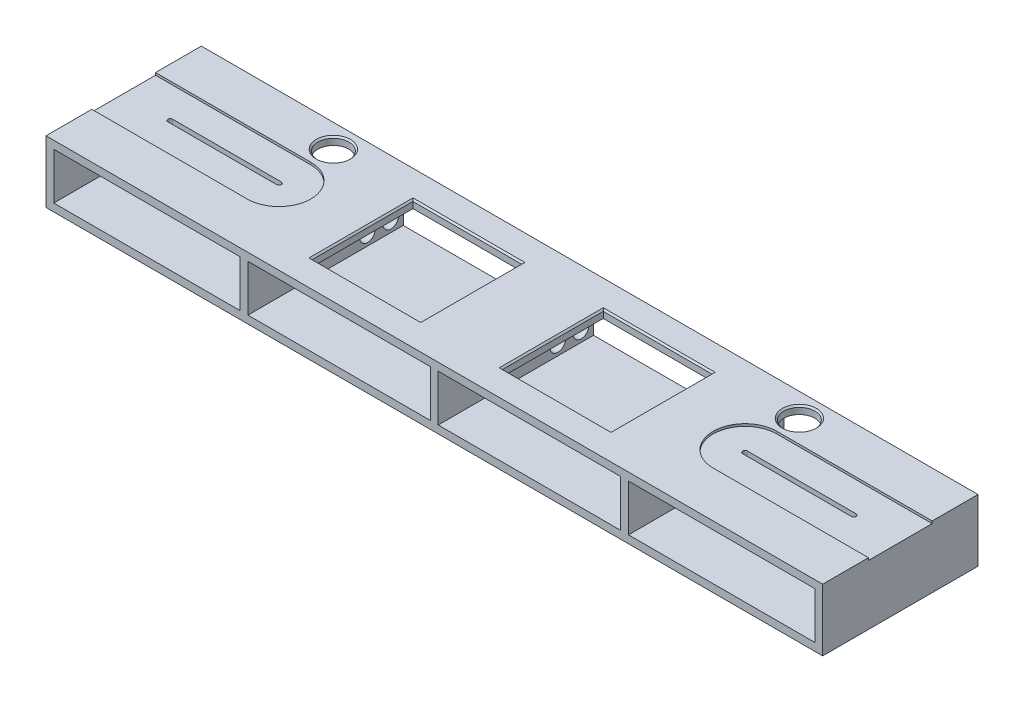
SolidWorks part; units mm, degrees
ref_plane "Alzado" through (0, 0, 0) normal (0, 0, 1) x (1, 0, 0)
ref_plane "Planta" through (0, 0, 0) normal (0, 1, 0) x (1, 0, 0)
ref_plane "Vista lateral" through (0, 0, 0) normal (1, 0, 0) x (0, 0, -1)
sketch "Croquis1" plane through (0, 0, 0) normal (0, 1, 0) x (1, 0, 0)
  line L1 (250, -50) -> (-250, -50)
  line L2 (250, -50) -> (250, 50)
  line L3 (250, 50) -> (-250, 50)
  line L4 (-250, -50) -> (-250, 50)
  line L5 (250, -50) -> (-250, 50) construction
  line L6 (250, 50) -> (-250, -50) construction
  point P0 (0, 0)
  dimension "D1" = 500
  dimension "D2" = 100
extrude "Saliente-Extruir1" add sketch "Croquis1" along normal blind 40
shell "Vaciado1" thickness 5
sketch "Croquis2" plane through (0, 0, 50) normal (0, 0, 1) x (1, 0, 0)
  line L0 (-245, 35) -> (125, 35) construction
  line L1 (-122.5, 35) -> (-122.5, 5)
  line L2 (-245, 5) -> (245, 5) construction
  line L3 (0, 35) -> (0, 5)
  line L4 (122.5, 35) -> (122.5, 5)
  line L6 (-125, 35) -> (-125, 5)
  line L7 (-2.5, 35) -> (-2.5, 5)
  line L8 (120, 35) -> (120, 5)
  line L10 (-120, 35) -> (-120, 5)
  line L11 (2.5, 35) -> (2.5, 5)
  line L12 (125, 35) -> (125, 5)
  line L14 (-125, 35) -> (-120, 35)
  line L15 (-125, 5) -> (-120, 5)
  line L16 (-2.5, 35) -> (2.5, 35)
  line L17 (-2.5, 5) -> (2.5, 5)
  line L18 (120, 35) -> (125, 35)
  line L19 (120, 5) -> (125, 5)
  line L22 (-245, 35) -> (-245, 5) construction
  line M10 (245, 5) -> (-245, 5)
  line M12 (-245, 35) -> (245, 35)
  dimension "D3" = 122.5
  dimension "D4" = 122.5
  dimension "D5" = 122.5
  dimension "D1" = 2.5
  dimension "D2" = 2.5
extrude "Saliente-Extruir2" add sketch "Croquis2" against normal blind 100 contours L6 L1 M12 M10 | L10 L1 M12 M10 | L7 L3 M12 M10 | L11 L3 M12 M10 | L8 L4 M12 M10 | L12 L4 M12 M10
sketch "Croquis3" plane through (0, 40, 0) normal (0, 1, 0) x (1, 0, 0)
  line L0 (-250, 50) -> (-250, -50) construction
  line L1 (-250, 20.5) -> (-150, 20.5)
  line L2 (-250, 20.5) -> (-250, -20.5)
  line L3 (-250, -20.5) -> (-150, -20.5)
  line L5 (250, -50) -> (250, 50) construction
  line L6 (250, 20.5) -> (150, 20.5)
  line L7 (250, 20.5) -> (250, -20.5)
  line L8 (250, -20.5) -> (150, -20.5)
  arc A0 (-150, 20.5) -> (-150, -20.5) centre (-150, 0) cw
  arc A1 (150, 20.5) -> (150, -20.5) centre (150, 0) ccw
  point P12 (-250, 0)
  point P13 (-250, 0)
  point P14 (250, 0)
  point P15 (250, 0)
  dimension "D1" = 41
  dimension "D2" = 41
  dimension "D3" = 100
  dimension "D4" = 100
extrude "Cortar-Extruir1" cut sketch "Croquis3" against normal blind 1.5
sketch "Croquis4" plane through (0, 38.5, 0) normal (0, 1, 0) x (1, 0, 0)
  line L0 (-150, 0) -> (-220, 0) construction
  line L1 (-150, -1.5) -> (-220, -1.5)
  line L2 (-150, 1.5) -> (-220, 1.5)
  line L3 (150, 0) -> (220, 0) construction
  line L4 (150, 1.5) -> (220, 1.5)
  line L5 (150, -1.5) -> (220, -1.5)
  arc A0 (-150, -1.5) -> (-150, 1.5) centre (-150, 0) ccw
  arc A1 (-220, 1.5) -> (-220, -1.5) centre (-220, 0) ccw
  arc A2 (150, 1.5) -> (150, -1.5) centre (150, 0) ccw
  arc A3 (220, -1.5) -> (220, 1.5) centre (220, 0) ccw
  point P4 (-185, 0)
  point P9 (185, 0)
  dimension "D3" = 1.5
  dimension "D4" = 1.5
  dimension "D1" = 70
  dimension "D2" = 70
extrude "Cortar-Extruir2" cut sketch "Croquis4" against normal blind 5
sketch "Croquis5" plane through (0, 40, 0) normal (0, 1, 0) x (1, 0, 0)
  line L0 (250, 50) -> (-250, 50) construction
  circle A0 centre (-150, 35) radius 10
  dimension "D1" = 20
  dimension "D2" = 15
extrude "Cortar-Extruir3" cut sketch "Croquis5" against normal blind 22.5
mirror "Simetría1" about plane through (0, 0, 0) normal (1, 0, 0) of "Cortar-Extruir3"
sketch "Croquis6" plane through (-125, 0, 0) normal (-1, 0, 0) x (0, 0, 1)
  line L0 (-50, 35) -> (50, 35) construction
  line L1 (-50, 40) -> (-50, 0) construction
  line L2 (-42, 27) -> (-27, 27) construction
  circle A0 centre (-42, 27) radius 5
  circle A1 centre (-27, 27) radius 5
  circle A2 centre (-27, 12) radius 5
  circle A3 centre (-42, 12) radius 5
  dimension "D1" = 10
  dimension "D2" = 8
  dimension "D3" = 8
  dimension "D6" = 15
  dimension "D4" = 2
  dimension "D5" = 2
extrude "Cortar-Extruir4" cut sketch "Croquis6" against normal blind 281.5
sketch "Croquis7" plane through (0, 40, 0) normal (0, 1, 0) x (1, 0, 0)
  line L0 (-2.5, 0) -> (-120, 0) construction
  line L1 (-2.5, 50) -> (-2.5, -50) construction
  line L2 (-120, 50) -> (-120, -50) construction
  line L3 (0, -22) -> (0, 22) construction
  line L4 (-26.25, -32.5) -> (-96.25, -32.5)
  line L5 (-26.25, -32.5) -> (-26.25, 32.5)
  line L6 (-26.25, 32.5) -> (-96.25, 32.5)
  line L7 (-96.25, -32.5) -> (-96.25, 32.5)
  line L8 (-26.25, -32.5) -> (-96.25, 32.5) construction
  line L9 (-26.25, 32.5) -> (-96.25, -32.5) construction
  line L10 (26.25, -32.5) -> (26.25, 32.5)
  line L11 (26.25, -32.5) -> (96.25, -32.5)
  line L12 (96.25, -32.5) -> (96.25, 32.5)
  line L13 (26.25, 32.5) -> (96.25, 32.5)
  point P6 (-61.25, 0)
  dimension "D1" = 70
  dimension "D2" = 65
extrude "Cortar-Extruir5" cut sketch "Croquis7" against normal blind 5
chamfer "Chaflán1" distance 1 angle 45 8 edges at (61.25, 40, -32.5) (26.25, 40, 0) (61.25, 40, 32.5) (96.25, 40, 0) (-61.25, 40, 32.5) (-26.25, 40, 0) (-96.25, 40, 0) (-61.25, 40, -32.5)
chamfer "Chaflán2" distance 1 angle 45 2 edges at (150, 40, -25) (-150, 40, -25)
